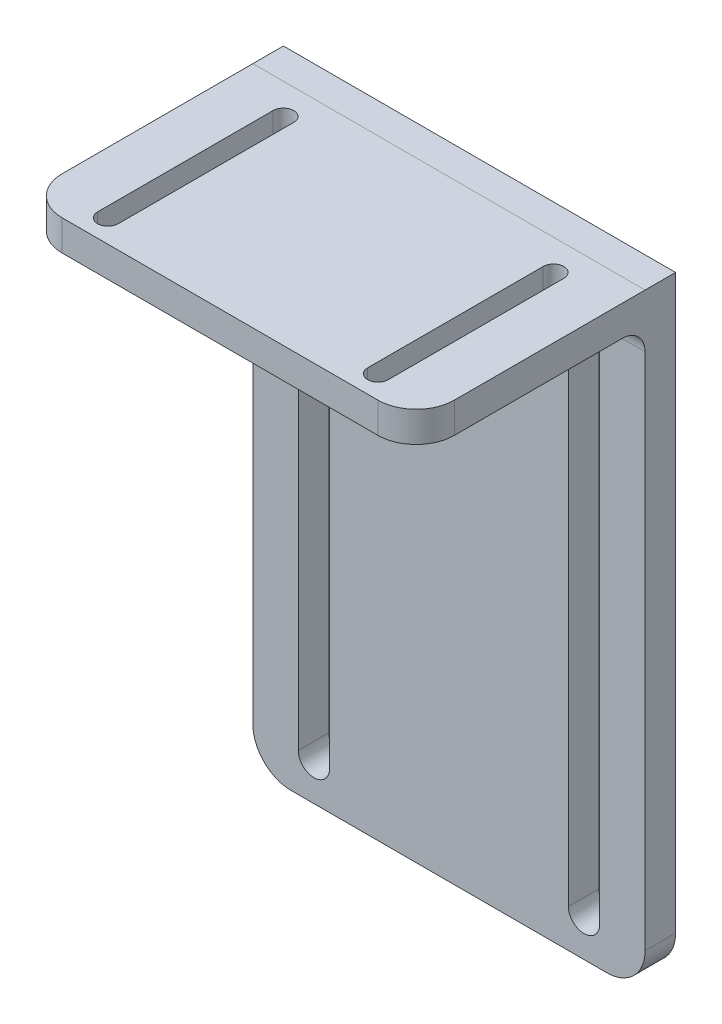
SolidWorks part; units mm, degrees
material "ABS"
ref_plane "Front Plane" through (0, 0, 0) normal (0, 0, 1) x (1, 0, 0)
ref_plane "Top Plane" through (0, 0, 0) normal (0, 1, 0) x (1, 0, 0)
ref_plane "Right Plane" through (0, 0, 0) normal (1, 0, 0) x (0, 0, -1)
sketch "Sketch2" plane through (0, 0, 0) normal (0, 0, 1) x (1, 0, 0)
  line L0 (8.0251, -7.544) -> (8.0251, -72.544) construction
  line L1 (0.0251, 2.456) -> (51.4251, 2.456)
  line L2 (0.0251, 2.456) -> (0.0251, -77.544)
  line L3 (0.0251, -77.544) -> (51.4251, -77.544)
  line L4 (51.4251, 2.456) -> (51.4251, -77.544)
  line L5 (10.0751, -7.544) -> (10.0751, -72.544)
  line L6 (5.9751, -7.544) -> (5.9751, -72.544)
  line L7 (43.4251, -72.544) -> (43.4251, -7.544) construction
  line L8 (41.3751, -72.544) -> (41.3751, -7.544)
  line L9 (45.4751, -72.544) -> (45.4751, -7.544)
  arc A0 (10.0751, -7.544) -> (5.9751, -7.544) centre (8.0251, -7.544) ccw
  arc A1 (5.9751, -72.544) -> (10.0751, -72.544) centre (8.0251, -72.544) ccw
  arc A2 (41.3751, -72.544) -> (45.4751, -72.544) centre (43.4251, -72.544) ccw
  arc A3 (45.4751, -7.544) -> (41.3751, -7.544) centre (43.4251, -7.544) ccw
  point P4 (8.0251, -40.044)
  point P11 (43.4251, -40.044)
  dimension "D1" = 80
  dimension "D2" = 51.4
  dimension "D3" = 8
  dimension "D4" = 8
  dimension "D5" = 4.1
  dimension "D6" = 4.1
  dimension "D7" = 10
  dimension "D8" = 10
  dimension "D9" = 5
  dimension "D10" = 5
extrude "Boss-Extrude1" add sketch "Sketch2" along normal blind 4
sketch "Sketch3" plane through (0, 0, 4) normal (0, 0, 1) x (1, 0, 0)
  line L1 (0.0251, 2.4561) -> (51.4251, 2.4561)
  line L2 (0.0251, 2.4561) -> (0.0251, -1.5439)
  line L3 (0.0251, -1.5439) -> (51.4251, -1.5439)
  line L4 (51.4251, 2.4561) -> (51.4251, -1.5439)
  dimension "D1" = 4
  dimension "D2" = 51.4
extrude "Boss-Extrude2" add sketch "Sketch3" along normal blind 30
sketch "Sketch4" plane through (0, 2.4561, 0) normal (0, 1, 0) x (1, 0, 0)
  line L0 (8.0251, -8) -> (8.0251, -31) construction
  line L1 (9.3751, -8) -> (9.3751, -31)
  line L2 (6.6751, -8) -> (6.6751, -31)
  line L3 (43.4251, -31) -> (43.4251, -8) construction
  line L4 (42.0751, -31) -> (42.0751, -8)
  line L5 (44.7751, -31) -> (44.7751, -8)
  line L6 (51.4251, -34) -> (0.0251, -34) construction
  line L7 (0.0251, -34) -> (0.0251, -4) construction
  line L8 (51.4251, -34) -> (51.4251, -4) construction
  line L9 (51.4251, -4) -> (0.0251, -4) construction
  arc A0 (9.3751, -8) -> (6.6751, -8) centre (8.0251, -8) ccw
  arc A1 (6.6751, -31) -> (9.3751, -31) centre (8.0251, -31) ccw
  arc A2 (42.0751, -31) -> (44.7751, -31) centre (43.4251, -31) ccw
  arc A3 (44.7751, -8) -> (42.0751, -8) centre (43.4251, -8) ccw
  point P2 (8.0251, -19.5)
  point P7 (43.4251, -19.5)
  dimension "D1" = 3
  dimension "D2" = 8
  dimension "D3" = 8
  dimension "D4" = 3
  dimension "D5" = 4
  dimension "D6" = 4
  dimension "D7" = 2.7
  dimension "D8" = 2.7
extrude "Cut-Extrude1" cut sketch "Sketch4" against normal through all
fillet "Fillet1" radius 5 4 edges at (0.0251, 0.4561, 34) (51.4251, 0.4561, 34) (51.4251, -77.544, 2) (0.0251, -77.544, 2)
fillet "Fillet2" radius 3 1 edges at (25.7251, -1.5439, 4)
